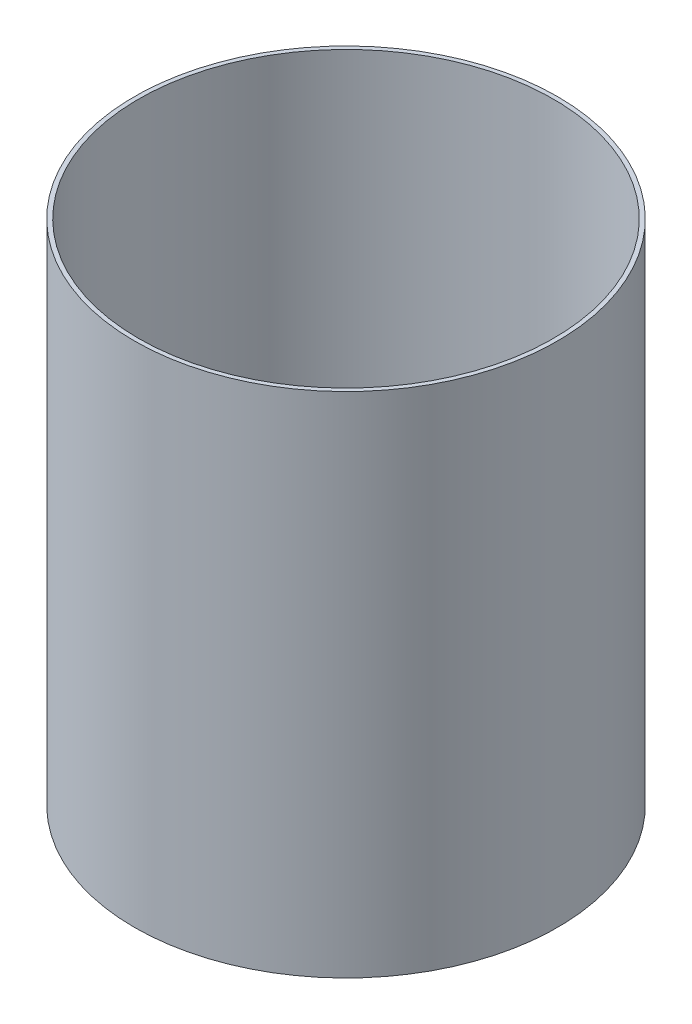
SolidWorks part; units mm, degrees
ref_plane "Front Plane" through (0, 0, 0) normal (0, 0, 1) x (1, 0, 0)
ref_plane "Top Plane" through (0, 0, 0) normal (0, 1, 0) x (1, 0, 0)
ref_plane "Right Plane" through (0, 0, 0) normal (1, 0, 0) x (0, 0, -1)
sketch "Sketch1" plane through (0, 0, 0) normal (0, 1, 0) x (1, 0, 0)
  circle A0 centre (0, 0) radius 125
extrude "Boss-Extrude1" add sketch "Sketch1" along normal blind 300
shell "Shell2" thickness 2.5
